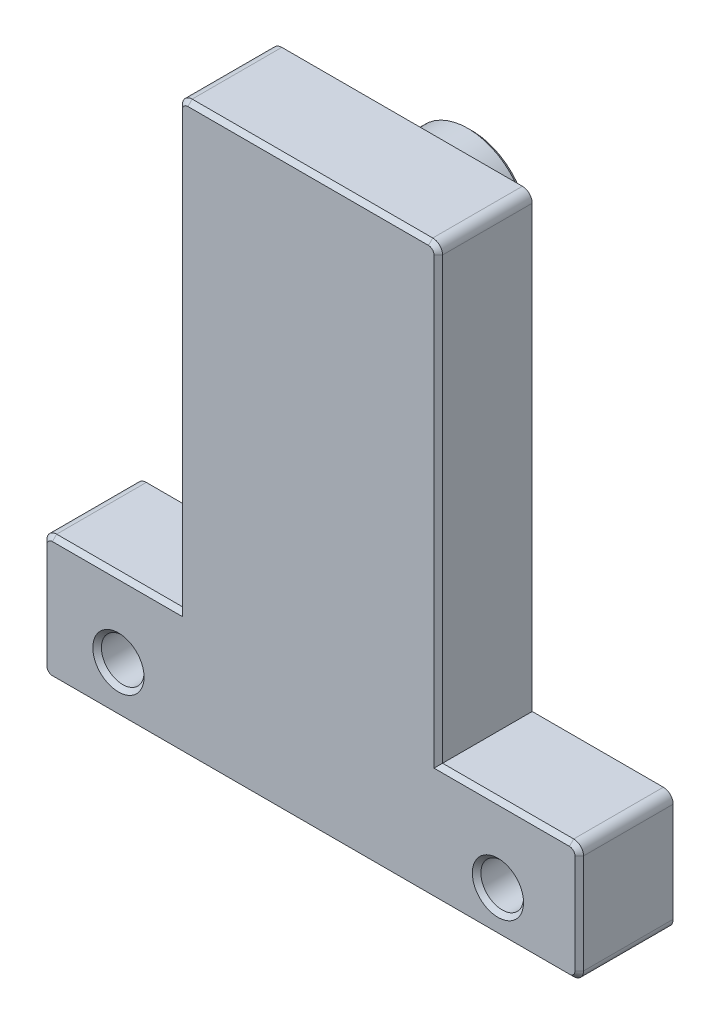
SolidWorks part; units mm, degrees
material "铜"
ref_plane "前视基准面" through (0, 0, 0) normal (0, 0, 1) x (1, 0, 0)
ref_plane "上视基准面" through (0, 0, 0) normal (0, 1, 0) x (1, 0, 0)
ref_plane "右视基准面" through (0, 0, 0) normal (1, 0, 0) x (0, 0, -1)
sketch "草图3" plane through (0, 0, 0) normal (0, 0, 1) x (1, 0, 0)
  line L0 (82.169, 69.088) -> (82.423, 69.088)
  line L1 (82.169, 69.088) -> (82.169, 69.469)
  line L2 (82.169, 69.469) -> (82.296, 69.596)
  line L3 (81.026, 69.596) -> (82.296, 69.596)
  line L4 (81.026, 69.088) -> (81.026, 69.596)
  line L5 (79.121, 69.088) -> (81.026, 69.088)
  line L6 (82.423, 69.088) -> (86.36, 69.088)
  line L7 (79.121, 69.088) -> (79.121, 69.596)
  line L8 (77.851, 69.596) -> (79.121, 69.596)
  line L9 (77.851, 69.088) -> (77.851, 69.596)
  line L10 (73.787, 69.088) -> (77.851, 69.088)
  line L11 (73.787, 69.088) -> (73.787, 72.009)
  line L12 (73.787, 72.009) -> (74.041, 72.009)
  line L13 (74.041, 72.009) -> (76.962, 72.009)
  line L14 (76.962, 72.009) -> (76.962, 82.423)
  line L15 (76.962, 82.423) -> (83.058, 82.423)
  line L16 (83.058, 71.882) -> (83.058, 82.423)
  line L17 (83.058, 71.882) -> (86.36, 71.882)
  line L18 (86.36, 69.088) -> (86.36, 71.882)
  circle A0 centre (82.169, 69.088) radius 0.0635
  circle A1 centre (82.423, 69.088) radius 0.0635
  circle A2 centre (82.169, 69.088) radius 0.0635
  circle A3 centre (82.169, 69.469) radius 0.0635
  circle A4 centre (82.169, 69.469) radius 0.0635
  circle A5 centre (82.296, 69.596) radius 0.0635
  circle A6 centre (81.026, 69.596) radius 0.0635
  circle A7 centre (82.296, 69.596) radius 0.0635
  circle A8 centre (81.026, 69.088) radius 0.0635
  circle A9 centre (81.026, 69.596) radius 0.0635
  circle A10 centre (79.121, 69.088) radius 0.0635
  circle A11 centre (81.026, 69.088) radius 0.0635
  circle A12 centre (82.423, 69.088) radius 0.0635
  circle A13 centre (86.36, 69.088) radius 0.0635
  circle A14 centre (79.121, 69.088) radius 0.0635
  circle A15 centre (79.121, 69.596) radius 0.0635
  circle A16 centre (77.851, 69.596) radius 0.0635
  circle A17 centre (79.121, 69.596) radius 0.0635
  circle A18 centre (77.851, 69.088) radius 0.0635
  circle A19 centre (77.851, 69.596) radius 0.0635
  circle A20 centre (73.787, 69.088) radius 0.0635
  circle A21 centre (77.851, 69.088) radius 0.0635
  circle A22 centre (73.787, 69.088) radius 0.0635
  circle A23 centre (73.787, 72.009) radius 0.0635
  circle A24 centre (73.787, 72.009) radius 0.0635
  circle A25 centre (74.041, 72.009) radius 0.0635
  circle A26 centre (74.041, 72.009) radius 0.0635
  circle A27 centre (76.962, 72.009) radius 0.0635
  circle A28 centre (76.962, 72.009) radius 0.0635
  circle A29 centre (76.962, 82.423) radius 0.0635
  circle A30 centre (76.962, 82.423) radius 0.0635
  circle A31 centre (83.058, 82.423) radius 0.0635
  circle A32 centre (83.058, 71.882) radius 0.0635
  circle A33 centre (83.058, 82.423) radius 0.0635
  circle A34 centre (83.058, 71.882) radius 0.0635
  circle A35 centre (86.36, 71.882) radius 0.0635
  circle A36 centre (86.36, 69.088) radius 0.0635
  circle A37 centre (86.36, 71.882) radius 0.0635
  circle A38 centre (80, 80) radius 1.2573
  circle A39 centre (81.2573, 80) radius 0.0635
  circle A40 centre (78.7427, 80) radius 0.0635
  circle A41 centre (84.455, 70.104) radius 0.7184
  circle A42 centre (85.1734, 70.104) radius 0.0635
  circle A43 centre (83.7366, 70.104) radius 0.0635
  circle A44 centre (75.565, 70.231) radius 0.5236
  circle A45 centre (76.0886, 70.231) radius 0.0635
  circle A46 centre (75.0414, 70.231) radius 0.0635
sketch "草图1" plane through (0, 0, 0) normal (0, 0, 1) x (1, 0, 0)
  line L0 (82.169, 69.088) -> (82.423, 69.088)
  line L1 (82.169, 69.088) -> (82.169, 69.469)
  line L2 (82.169, 69.469) -> (82.296, 69.596)
  line L3 (81.026, 69.596) -> (82.296, 69.596)
  line L4 (81.026, 69.088) -> (81.026, 69.596)
  line L5 (79.121, 69.088) -> (81.026, 69.088)
  line L6 (82.423, 69.088) -> (86.36, 69.088)
  line L7 (79.121, 69.088) -> (79.121, 69.596)
  line L8 (77.851, 69.596) -> (79.121, 69.596)
  line L9 (77.851, 69.088) -> (77.851, 69.596)
  line L10 (73.787, 69.088) -> (77.851, 69.088)
  line L11 (73.787, 69.088) -> (73.787, 72.009)
  line L12 (73.787, 72.009) -> (74.041, 72.009)
  line L13 (74.041, 72.009) -> (76.962, 72.009)
  line L14 (76.962, 72.009) -> (76.962, 82.423)
  line L15 (76.962, 82.423) -> (83.058, 82.423)
  line L16 (83.058, 71.882) -> (83.058, 82.423)
  line L17 (83.058, 71.882) -> (86.36, 71.882)
  line L18 (86.36, 69.088) -> (86.36, 71.882)
  circle A0 centre (82.169, 69.088) radius 0.0635
  circle A1 centre (82.423, 69.088) radius 0.0635
  circle A2 centre (82.169, 69.088) radius 0.0635
  circle A3 centre (82.169, 69.469) radius 0.0635
  circle A4 centre (82.169, 69.469) radius 0.0635
  circle A5 centre (82.296, 69.596) radius 0.0635
  circle A6 centre (81.026, 69.596) radius 0.0635
  circle A7 centre (82.296, 69.596) radius 0.0635
  circle A8 centre (81.026, 69.088) radius 0.0635
  circle A9 centre (81.026, 69.596) radius 0.0635
  circle A10 centre (79.121, 69.088) radius 0.0635
  circle A11 centre (81.026, 69.088) radius 0.0635
  circle A12 centre (82.423, 69.088) radius 0.0635
  circle A13 centre (86.36, 69.088) radius 0.0635
  circle A14 centre (79.121, 69.088) radius 0.0635
  circle A15 centre (79.121, 69.596) radius 0.0635
  circle A16 centre (77.851, 69.596) radius 0.0635
  circle A17 centre (79.121, 69.596) radius 0.0635
  circle A18 centre (77.851, 69.088) radius 0.0635
  circle A19 centre (77.851, 69.596) radius 0.0635
  circle A20 centre (73.787, 69.088) radius 0.0635
  circle A21 centre (77.851, 69.088) radius 0.0635
  circle A22 centre (73.787, 69.088) radius 0.0635
  circle A23 centre (73.787, 72.009) radius 0.0635
  circle A24 centre (73.787, 72.009) radius 0.0635
  circle A25 centre (74.041, 72.009) radius 0.0635
  circle A26 centre (74.041, 72.009) radius 0.0635
  circle A27 centre (76.962, 72.009) radius 0.0635
  circle A28 centre (76.962, 72.009) radius 0.0635
  circle A29 centre (76.962, 82.423) radius 0.0635
  circle A30 centre (76.962, 82.423) radius 0.0635
  circle A31 centre (83.058, 82.423) radius 0.0635
  circle A32 centre (83.058, 71.882) radius 0.0635
  circle A33 centre (83.058, 82.423) radius 0.0635
  circle A34 centre (83.058, 71.882) radius 0.0635
  circle A35 centre (86.36, 71.882) radius 0.0635
  circle A36 centre (86.36, 69.088) radius 0.0635
  circle A37 centre (86.36, 71.882) radius 0.0635
  circle A38 centre (84.455, 70.104) radius 0.7184
  circle A39 centre (85.1734, 70.104) radius 0.0635
  circle A40 centre (83.7366, 70.104) radius 0.0635
  circle A41 centre (75.565, 70.231) radius 0.5236
  circle A42 centre (76.0886, 70.231) radius 0.0635
  circle A43 centre (75.0414, 70.231) radius 0.0635
sketch "草图2" plane through (0, 0, 0) normal (0, 0, 1) x (1, 0, 0)
  line L0 (73.787, 72.009) -> (76.962, 72.009)
  line L1 (76.962, 72.009) -> (76.962, 82.423)
  line L2 (76.962, 82.423) -> (83.058, 82.423)
  line L3 (83.058, 82.423) -> (83.058, 71.882)
  line L4 (83.058, 71.882) -> (86.36, 71.882)
  line L5 (86.36, 71.882) -> (86.36, 69.088)
  line L6 (73.787, 72.009) -> (73.787, 69.088)
  line L7 (73.787, 69.088) -> (77.851, 69.088) construction
  line L11 (82.423, 69.088) -> (86.36, 69.088) construction
  line L12 (82.804, 69.088) -> (86.36, 69.088)
  line L15 (77.343, 69.088) -> (73.787, 69.088)
  line L16 (77.343, 69.088) -> (82.804, 69.088)
extrude "凸台-拉伸1" add sketch "草图2" along normal blind 2.2
fillet "圆角1" radius 0.23 6 edges at (73.787, 69.088, 1.1) (73.787, 72.009, 1.1) (76.962, 82.423, 1.1) (83.058, 82.423, 1.1) (86.36, 69.088, 1.1) (86.36, 71.882, 1.1)
sketch "草图4" plane through (0, 0, 0) normal (0, 0, 1) x (1, 0, 0)
  circle A0 centre (80, 80) radius 1.41
extrude "凸台-拉伸2" add sketch "草图4" against normal blind 1.65 from surface at 0 starting at face at (80.0463, 74.0966, 0)
chamfer "倒角1" distance 0.1 angle 45 15 edges at (73.8544, 71.9416, 2.2) (75.4895, 72.009, 2.2) (76.962, 77.101, 2.2) (77.0294, 82.3556, 2.2) (80.01, 82.423, 2.2) (82.9906, 82.3556, 2.2) (83.058, 77.0375, 2.2) (84.594, 71.882, 2.2) (86.2926, 71.8146, 2.2) (86.36, 70.485, 2.2) (86.2926, 69.1554, 2.2) (80.0735, 69.088, 2.2) (73.8544, 69.1554, 2.2) (73.787, 70.5485, 2.2) (78.59, 80, -1.65)
sketch "草图5" plane through (0, 0, 0) normal (0, 0, 1) x (1, 0, 0)
  circle A0 centre (75.565, 70.231) radius 0.5
  circle A1 centre (84.455, 70.104) radius 0.5
extrude "切除-拉伸1" cut sketch "草图5" along normal up to surface (2.2 mm away) from surface at 0 up to face at (80.0463, 74.0651, 2.2) starting at face at (78.59, 80, 0)
chamfer "倒角2" distance 0.1 angle 45 2 edges at (83.955, 70.104, 2.2) (75.065, 70.231, 2.2)
